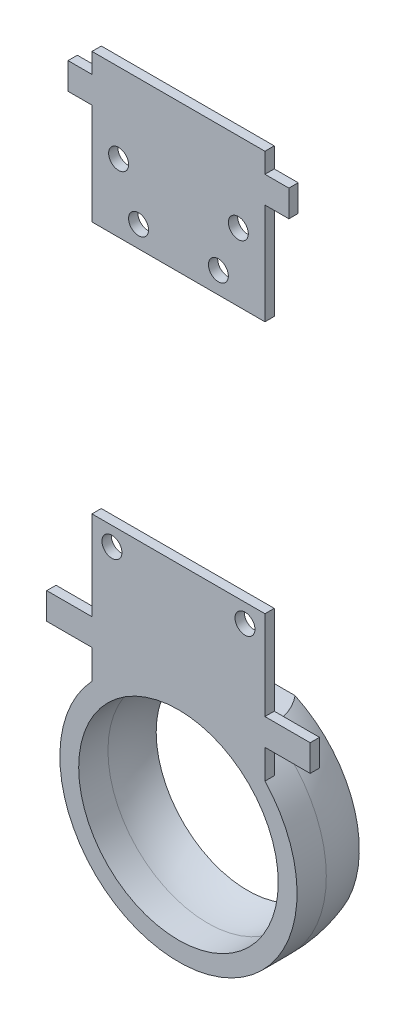
SolidWorks part; units mm, degrees
ref_plane "Front Plane" through (0, 0, 0) normal (0, 0, 1) x (1, 0, 0)
ref_plane "Top Plane" through (0, 0, 0) normal (0, 1, 0) x (1, 0, 0)
ref_plane "Right Plane" through (0, 0, 0) normal (1, 0, 0) x (0, 0, -1)
sketch "Sketch1" plane through (0, 0, 0) normal (0, 0, 1) x (1, 0, 0)
  line L0 (-45, 130) -> (45, 130) construction
  line L1 (0, 225) -> (0, 35) construction
  line L2 (45, 225) -> (-45, 225) construction
  line L3 (10, 161.5385) -> (32.5, 174.5288)
  line L4 (45, 35) -> (45, 225)
  line L5 (45, 225) -> (-45, 225)
  line L6 (-45, 225) -> (-45, 35)
  line L7 (-45, 35) -> (45, 35)
  line L8 (45, 35) -> (45, 225)
  line L9 (45, 225) -> (-45, 225)
  line L10 (-45, 225) -> (-45, 35)
  line L11 (-45, 35) -> (45, 35)
  line L12 (-32.5, 27.5) -> (32.5, 27.5) construction
  line L13 (-32.5, 27.5) -> (-32.5, 90.2722)
  line L14 (-32.5, 232.5) -> (32.5, 232.5)
  line L15 (32.5, 27.5) -> (32.5, 90.2722)
  line L16 (-32.5, 27.5) -> (32.5, 232.5) construction
  line L17 (-32.5, 232.5) -> (32.5, 27.5) construction
  line L19 (-10, 98.4615) -> (-10, 161.5385)
  line L21 (10, 98.4615) -> (10, 161.5385)
  line L22 (-10, 98.4615) -> (10, 161.5385) construction
  line L23 (-10, 161.5385) -> (10, 98.4615) construction
  line L24 (-10, 161.5385) -> (-32.5, 174.5288)
  line L25 (-10, 98.4615) -> (-32.5, 90.2722)
  line L26 (10, 98.4615) -> (32.5, 90.2722)
  line L27 (-32.5, 174.5288) -> (-32.5, 232.5)
  line L28 (32.5, 174.5288) -> (32.5, 232.5)
  line L29 (-45, 35) -> (0, -42.9423) construction
  line L30 (0, -42.9423) -> (45, 35) construction
  line L31 (0, -42.9423) -> (0, -3) construction
  line L32 (0, -3) -> (45, 35) construction
  line L33 (0, -3) -> (-45, 35) construction
  line L34 (32.5, 27.5) -> (32.5, 35)
  line L35 (32.5, 35) -> (45, 35)
  line L36 (-43.5, 38.5) -> (45, 38.5) construction
  line L37 (-3, -40.3798) -> (3, -40.3798)
  line L38 (-3, -40.3798) -> (-3, 34.3798)
  line L39 (-3, 34.3798) -> (3, 34.3798)
  line L40 (3, -40.3798) -> (3, 34.3798)
  line L41 (-3, -40.3798) -> (3, 34.3798) construction
  line L42 (-3, 34.3798) -> (3, -40.3798) construction
  line L43 (-37.3798, 0) -> (37.3798, 0)
  line L44 (-37.3798, 0) -> (-37.3798, -6)
  line L45 (-37.3798, -6) -> (37.3798, -6)
  line L46 (37.3798, 0) -> (37.3798, -6)
  line L47 (-37.3798, 0) -> (37.3798, -6) construction
  line L48 (-37.3798, -6) -> (37.3798, 0) construction
  line L49 (-32.5, 38.5) -> (-49.5, 38.5)
  line L50 (-32.5, 38.5) -> (-32.5, 48.5)
  line L51 (-32.5, 48.5) -> (-49.5, 48.5)
  line L52 (-49.5, 38.5) -> (-49.5, 48.5)
  line L53 (32.5, 48.5) -> (49.5, 48.5)
  line L54 (-32.5, 225) -> (-41.5, 225)
  line L55 (-32.5, 225) -> (-32.5, 215)
  line L56 (-32.5, 215) -> (-41.5, 215)
  line L57 (-41.5, 225) -> (-41.5, 215)
  line L58 (49.5, 38.5) -> (49.5, 48.5)
  line L59 (32.5, 38.5) -> (49.5, 38.5)
  line L60 (32.5, 38.5) -> (32.5, 48.5)
  line L61 (32.5, 215) -> (41.5, 215)
  line L62 (41.5, 225) -> (41.5, 215)
  line L63 (32.5, 225) -> (41.5, 225)
  line L64 (32.5, 225) -> (32.5, 215)
  circle A0 centre (-25, 75) radius 3.75 construction
  circle A1 centre (-22.5, 202.5) radius 3.75 construction
  circle A2 centre (25, 75) radius 3.75 construction
  circle A3 centre (22.5, 202.5) radius 3.75 construction
  circle A4 centre (-25, 75) radius 3.75
  circle A5 centre (-22.5, 202.5) radius 3.75
  circle A6 centre (25, 75) radius 3.75
  circle A7 centre (22.5, 202.5) radius 3.75
  circle A8 centre (15, 185) radius 3.75 construction
  circle A9 centre (-15, 185) radius 3.75 construction
  circle A10 centre (15, 185) radius 3.75
  circle A11 centre (-15, 185) radius 3.75
  circle A13 centre (0, -3) radius 37.5
  arc A14 (-32.5, 27.5) -> (32.5, 27.5) centre (0, -3) ccw
  point P22 (0, 130)
  point P27 (0, 130)
  dimension "D13" = 75
  dimension "D2" = 7.5
  dimension "D3" = 65
  dimension "D4" = 20
  dimension "D5" = 120
  dimension "D6" = 120
  dimension "D7" = 110
  dimension "D8" = 110
  dimension "D9" = 35
  dimension "D10" = 60
  dimension "D11" = 60
  dimension "D12" = 38
  dimension "D14" = 6
  dimension "D15" = 10
  dimension "D16" = 17
  dimension "D17" = 10
  dimension "D18" = 9
  dimension "D1" = 0
extrude "Boss-Extrude1" add sketch "Sketch1" along normal blind 3.5 contours L3 L28 L9 L27 L24 L19 L25 L13 L11 L15 L26 L21 A11 A10 A7 A6 A5 A4 | L9 L28 L14 L27 | L13 A14 L15 L11 A13 | L9 L57 L56 L27 | L62 L9 L28 L61 | L52 L49 L10 L51 | L13 L51 L10 L49 | L15 L59 L8 L53 | L8 L59 L58 L53
sketch "Sketch2" plane through (0, 0, 0) normal (1, 0, 0) x (0, 0, -1)
  line L0 (22.5, 38.9702) -> (22.5, -44.9702)
  line L2 (7.5, -40.5) -> (0, -40.5)
  line L4 (7.5, 38.9702) -> (22.5, 38.9702)
  line L5 (7.5, -40.5) -> (7.5, -47.5702)
  line L6 (0, -3) -> (138.4206, -3) construction
  line L7 (0, -47.5702) -> (0, 27.5) construction
  line L8 (7.5, 38.9702) -> (0, 38.9702)
  line L9 (0, 38.5) -> (0, 48.5) construction
  line L10 (0, 38.9702) -> (0, 34.5)
  line L11 (0, 27.5) -> (0, 38.5) construction
  line L12 (0, 34.5) -> (7.5, 34.5)
  line L13 (7.5, -47.5702) -> (0, -47.5702)
  line L14 (0, -47.5702) -> (0, -40.5)
  line L15 (0, -47.5702) -> (0, 27.5) construction
  arc A0 (7.5, 34.5) -> (7.5, -40.5) centre (7.5, -3) cw
  arc A1 (7.5, -47.5702) -> (22.5, 38.9702) centre (7.5, -3) ccw
  dimension "D1" = 22.5
  dimension "D2" = 37.5
  dimension "D3" = 7.5
revolve "Revolve1" add sketch "Sketch2" angle 360 about L6
sketch "Sketch3" plane through (32.5, 0, 0) normal (1, 0, 0) x (0, 0, -1)
  line L0 (0, 27.5) -> (0, 38.5) construction
  line L1 (0, 35) -> (40.0075, 35)
  line L2 (0, 35) -> (0, 65.6842)
  line L3 (0, 65.6842) -> (40.0075, 65.6842)
  line L4 (40.0075, 35) -> (40.0075, 65.6842)
  line L5 (5, 35) -> (0, 35) construction
extrude "Cut-Extrude1" cut sketch "Sketch3" against normal through all both and the other way through all
ref_plane "Plane1" through (0, 130, 0) normal (0, 1, 0) x (1, 0, 0)
sketch "Sketch4" plane through (0, 130, 0) normal (0, 1, 0) x (1, 0, 0)
  line L0 (50, -3.5) -> (50, 26.5)
  line L1 (50, 26.5) -> (45, 26.5)
  line L2 (45, 26.5) -> (45, 0)
  line L8 (45, 0) -> (10, 0)
  line L9 (10, 0) -> (10, -3.5)
  line L10 (10, -3.5) -> (50, -3.5)
  dimension "D1" = 3.5
  dimension "D2" = 35
  dimension "D3" = 40
  dimension "D4" = 30
extrude "Boss-Extrude2" add sketch "Sketch4" along normal mid plane 7.5
mirror "Mirror1" about plane through (0, 0, 0) normal (1, 0, 0) of "Boss-Extrude2"
sketch "Sketch5" plane through (0, 0, 3.5) normal (0, 0, 1) x (1, 0, 0)
  line L0 (-50, 176.2294) -> (-64.8, 178.4878) construction
  line L1 (55.0959, 81.9778) -> (-54.9041, 81.9778)
  line L2 (55.0959, 81.9778) -> (55.0959, 176.9778)
  line L3 (55.0959, 176.9778) -> (-54.9041, 176.9778)
  line L4 (-54.9041, 81.9778) -> (-54.9041, 176.9778)
  line L5 (55.0959, 81.9778) -> (-54.9041, 176.9778) construction
  line L6 (55.0959, 176.9778) -> (-54.9041, 81.9778) construction
  line L7 (50, 130) -> (-50, 130) construction
  line L8 (50, 133.75) -> (50, 126.25) construction
  line L9 (-50, 133.75) -> (-50, 126.25) construction
  line L10 (0, 0) -> (0, 282.7487) construction
  point P0 (0.0959, 129.4778)
  point P16 (0, 0)
  dimension "D1" = 95
  dimension "D2" = 110
extrude "Cut-Extrude2" cut sketch "Sketch5" against normal blind 50
